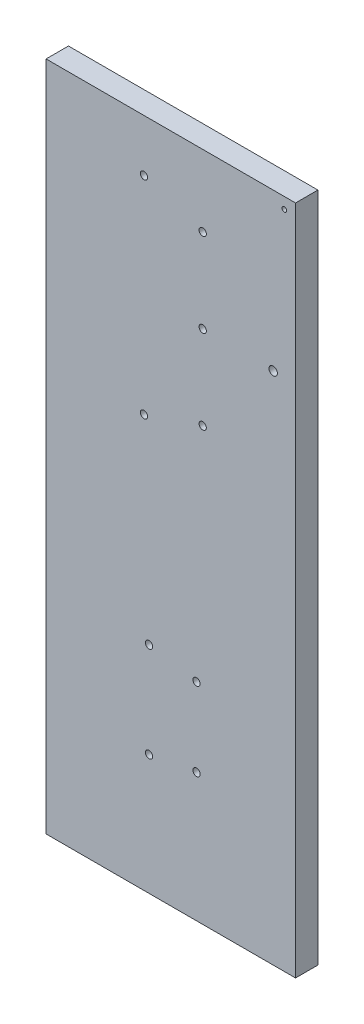
SolidWorks part; units mm, degrees
ref_plane "Front" through (0, 0, 0) normal (0, 0, 1) x (1, 0, 0)
ref_plane "Top" through (0, 0, 0) normal (0, 1, 0) x (1, 0, 0)
ref_plane "Right" through (0, 0, 0) normal (1, 0, 0) x (0, 0, -1)
sketch "Sketch1" plane through (0, 0, 0) normal (0, 0, 1) x (1, 0, 0)
  line L1 (0, 0) -> (223, 0)
  line L2 (0, 0) -> (0, 600)
  line L3 (0, 600) -> (223, 600)
  line L4 (223, 0) -> (223, 600)
  dimension "D1" = 223
  dimension "D2" = 600
extrude "Boss-Extrude1" add sketch "Sketch1" along normal blind 20
hole_wizard "CBORE for M6 Hex Socket Head Cap Screw1" positions "Sketch3" profile "Sketch2" counterbore size "M6" standard "ISO" end condition through all
sketch "Sketch3" plane through (0, 0, 0) normal (0, 0, -1) x (-1, 0, 0)
  line L0 (0, 600) -> (0, 0) construction
  line L1 (0, 0) -> (-223, 0) construction
  point P0 (-134.5, 115)
  point P1 (-134.5, 185)
  point P3 (-92, 107.5)
  point P5 (-92, 192.5)
  dimension "D1" = 92
  dimension "D2" = 42.5
  dimension "D3" = 107.5
  dimension "D4" = 7.5
  dimension "D5" = 70
  dimension "D6" = 7.5
sketch "Sketch2" plane through (134.5, 115, 0) normal (1, 0, 0) x (0, 1, 0)
  line L0 (0, 0) -> (0, 20)
  line L1 (0, 20) -> (3.25, 20)
  line L3 (3.25, 20) -> (3.25, 10)
  line L4 (3.25, 10) -> (7.5, 10)
  line L5 (7.5, 10) -> (7.5, 0)
  line L7 (7.5, 0) -> (0, 0)
  line L11 (0, -6.35) -> (0, 107.95) construction
  dimension "Thru Hole Dia." = 6.5
  dimension "Thru Hole Depth" = 20
  dimension "C'Bore Dia." = 15
  dimension "C'Bore Depth" = 10
hole_wizard "CBORE for M6 Hex Socket Head Cap Screw2" positions "Sketch5" profile "Sketch4" counterbore size "M6" standard "ISO" end condition through all
sketch "Sketch5" plane through (0, 0, 0) normal (0, 0, -1) x (-1, 0, 0)
  line L0 (0, 600) -> (0, 0) construction
  line L1 (0, 0) -> (-223, 0) construction
  point P0 (-87.5, 368.5)
  point P1 (-87.5, 553.5)
  point P3 (-140, 386)
  point P5 (-140, 461)
  point P7 (-140, 536)
  dimension "D1" = 87.5
  dimension "D2" = 52.5
  dimension "D3" = 368.5
  dimension "D4" = 17.5
  dimension "D5" = 75
  dimension "D6" = 75
  dimension "D7" = 17.5
sketch "Sketch4" plane through (87.5, 368.5, 0) normal (1, 0, 0) x (0, 1, 0)
  line L0 (0, 0) -> (0, 20)
  line L1 (0, 20) -> (3.25, 20)
  line L3 (3.25, 20) -> (3.25, 10)
  line L4 (3.25, 10) -> (7.5, 10)
  line L5 (7.5, 10) -> (7.5, 0)
  line L7 (7.5, 0) -> (0, 0)
  line L11 (0, -6.35) -> (0, 107.95) construction
  dimension "Thru Hole Dia." = 6.5
  dimension "Thru Hole Depth" = 20
  dimension "C'Bore Dia." = 15
  dimension "C'Bore Depth" = 10
sketch "Sketch6" plane through (0, 0, 20) normal (0, 0, 1) x (1, 0, 0)
  line L0 (0, 0) -> (223, 0) construction
  line L1 (0, 600) -> (0, 0) construction
  circle A0 centre (203, 460) radius 3.75
  dimension "D1" = 7.5
  dimension "D2" = 460
  dimension "D3" = 203
extrude "Cut-Extrude1" cut sketch "Sketch6" against normal through all
hole_wizard "M5 Tapped Hole1" positions "Sketch8" profile "Sketch7" tap size "M5" standard "ISO"
sketch "Sketch8" plane through (0, 0, 20) normal (0, 0, 1) x (1, 0, 0)
  line L0 (0, 600) -> (0, 0) construction
  line L1 (0, 0) -> (223, 0) construction
  point P0 (213, 590)
  dimension "D1" = 213
  dimension "D2" = 590
cosmetic thread "Hole Thread1" parameters "D1"=10, "D2"=5
sketch "Sketch7" plane through (213, 590, 20) normal (1, 0, 0) x (0, -1, 0)
  line L0 (0, 0) -> (0, 13.6618)
  line L1 (0, 13.6618) -> (2.1, 12.4)
  line L2 (2.1, 12.4) -> (2.1, 0)
  line L5 (2.1, 0) -> (0, 0)
  line L10 (0, 13.6618) -> (-2.1, 12.4) construction
  line L11 (0, -6.35) -> (0, 107.95) construction
  dimension "Tap Drill Dia." = 4.2
  dimension "Tap Drill Depth" = 12.4
  dimension "Drill Angle" = 118
